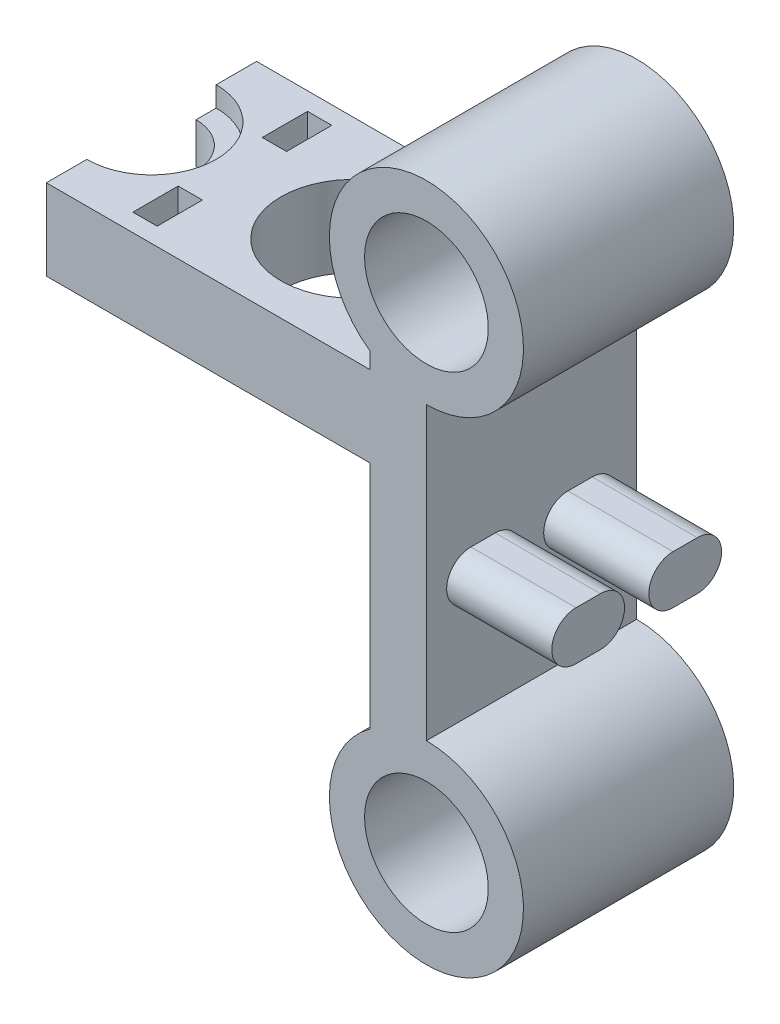
SolidWorks part; units mm, degrees
material "ABS"
ref_plane "Plano frontal" through (0, 0, 0) normal (0, 0, 1) x (1, 0, 0)
ref_plane "Plano superior" through (0, 0, 0) normal (0, 1, 0) x (1, 0, 0)
ref_plane "Plano direito" through (0, 0, 0) normal (1, 0, 0) x (0, 0, -1)
sketch "Esboço1" plane through (0, 0, 0) normal (0, 0, 1) x (1, 0, 0)
  line L0 (0, 30) -> (0, -30) construction
  line L1 (-7, 20.2532) -> (-7, 18.2532)
  line L2 (0, 18) -> (0, -18)
  line L3 (-7, 30) -> (-7, -30) construction
  line L4 (0, 30) -> (0, -30) construction
  line L5 (-47, 8.2532) -> (-7, 8.2532)
  line L6 (-47, 8.2532) -> (-47, 18.2532)
  line L7 (-47, 18.2532) -> (-7, 18.2532)
  line L8 (-7, 8.2532) -> (-7, -20.2532)
  circle A0 centre (0, 30) radius 7.65
  circle A1 centre (0, -30) radius 7.65
  arc A2 (0, 18) -> (-7, 20.2532) centre (0, 30) ccw
  arc A3 (-7, -20.2532) -> (0, -18) centre (0, -30) ccw
  point P4 (0, 0)
  dimension "D3" = 60
  dimension "D4" = 15.3
  dimension "D5" = 24
  dimension "D8" = 2
  dimension "D6" = 40
  dimension "D7" = 10
  dimension "D1" = 7
  dimension "D2" = 0
extrude "Ressalto-extrusão1" add sketch "Esboço1" along normal blind 26
sketch "Esboço3" plane through (-47, 0, 0) normal (-1, 0, 0) x (0, 0, 1)
  line L0 (13, 18.2532) -> (13, 8.2532) construction
  line L1 (26, 18.2532) -> (0, 18.2532) construction
  line L3 (13, 18.2532) -> (21, 18.2532)
  line L4 (21, 18.2532) -> (21, 15.7532)
  line L5 (21, 15.7532) -> (18.5, 15.7532)
  line L6 (18.5, 15.7532) -> (18.5, 10.7532)
  line L7 (18.5, 10.7532) -> (21, 10.7532)
  line L8 (21, 10.7532) -> (21, 8.2532)
  line L10 (21, 8.2532) -> (13, 8.2532)
  line L11 (13, 18.2532) -> (13, 8.2532)
  point P6 (18.5, 13.2532)
  dimension "D1" = 5
  dimension "D2" = 5.5
  dimension "D3" = 8
  dimension "D4" = 2.5
revolve "Corte-Revolução1" cut sketch "Esboço3" angle 360 about L0
sketch "Esboço4" plane through (-47, 0, 0) normal (-1, 0, 0) x (0, 0, 1)
  line L0 (13, 18.2532) -> (13, -18.4674) construction
  line L1 (26, 18.2532) -> (0, 18.2532) construction
  line L3 (7.5, 15.7532) -> (7.5, 10.7532) construction
  circle A0 centre (5, 13.2532) radius 1.75
  circle A1 centre (21, 13.2532) radius 1.75
  point P11 (7.5, 13.2532)
  dimension "D2" = 3.5
  dimension "D1" = 16
extrude "Corte-extrusão1" cut sketch "Esboço4" against normal blind 20
sketch "Esboço5" plane through (0, 18.2532, 0) normal (0, 1, 0) x (1, 0, 0)
  line L0 (-47, -5) -> (-37, -5) construction
  line L1 (-47, -5) -> (-47, 0) construction
  line L2 (-38.5, -2.2) -> (-35.5, -2.2)
  line L3 (-38.5, -2.2) -> (-38.5, -7.8)
  line L4 (-38.5, -7.8) -> (-35.5, -7.8)
  line L5 (-35.5, -2.2) -> (-35.5, -7.8)
  line L6 (-38.5, -2.2) -> (-35.5, -7.8) construction
  line L7 (-38.5, -7.8) -> (-35.5, -2.2) construction
  line L8 (-47, -13) -> (-16.3815, -13) construction
  line L9 (-38.5, -18.2) -> (-35.5, -23.8) construction
  line L10 (-38.5, -23.8) -> (-35.5, -18.2) construction
  line L11 (-47, -21) -> (-37, -21) construction
  line L12 (-35.5, -23.8) -> (-35.5, -18.2)
  line L13 (-38.5, -18.2) -> (-35.5, -18.2)
  line L14 (-38.5, -23.8) -> (-38.5, -18.2)
  line L15 (-38.5, -23.8) -> (-35.5, -23.8)
  dimension "D1" = 10
  dimension "D2" = 5.6
  dimension "D3" = 3
  dimension "D4" = 16
extrude "Corte-extrusão2" cut sketch "Esboço5" against normal blind 25
sketch "Esboço6" plane through (0, 0, 0) normal (1, 0, 0) x (0, 0, -1)
  line L0 (-13, 18) -> (-13, -18) construction
  line L1 (-26, 18) -> (0, 18) construction
  line L2 (-26, -18) -> (0, -18) construction
  line L3 (-20.9737, 0) -> (-5.0263, 0) construction
  line L4 (-49.8119, -6) -> (-16.3807, -6) construction
  line L5 (-17.5, -3) -> (-20.5, -3) construction
  line L6 (-17.5, -6) -> (-20.5, -6)
  line L7 (-17.5, 0) -> (-20.5, 0)
  line L8 (-8.5, -3) -> (-5.5, -3) construction
  line L9 (-8.5, -6) -> (-5.5, -6)
  line L10 (-8.5, 0) -> (-5.5, 0)
  circle A0 centre (-49.8119, 0) radius 6 construction
  arc A1 (-17.5, -6) -> (-17.5, 0) centre (-17.5, -3) ccw
  arc A2 (-20.5, 0) -> (-20.5, -6) centre (-20.5, -3) ccw
  arc A3 (-8.5, -6) -> (-8.5, 0) centre (-8.5, -3) cw
  arc A4 (-5.5, 0) -> (-5.5, -6) centre (-5.5, -3) cw
  point P10 (-13, 0)
  point P16 (-19, -3)
  point P24 (-7, -3)
  dimension "D1" = 12
  dimension "D2" = 3
  dimension "D3" = 3
  dimension "D4" = 3
extrude "Ressalto-extrusão2" add sketch "Esboço6" along normal blind 13
sketch "Esboço7" plane through (0, 18.2532, 0) normal (0, 1, 0) x (1, 0, 0)
  line L0 (-47, -26) -> (-47, -21) construction
  circle A0 centre (-22, -13) radius 9
  arc A1 (-47, -21) -> (-47, -5) centre (-47, -13) ccw construction
  point P2 (0, 0)
  point P6 (-39, -13)
  point P9 (-47, -23.5)
  dimension "D1" = 18
  dimension "D2" = 25
extrude "Corte-extrusão3" cut sketch "Esboço7" against normal blind 10
